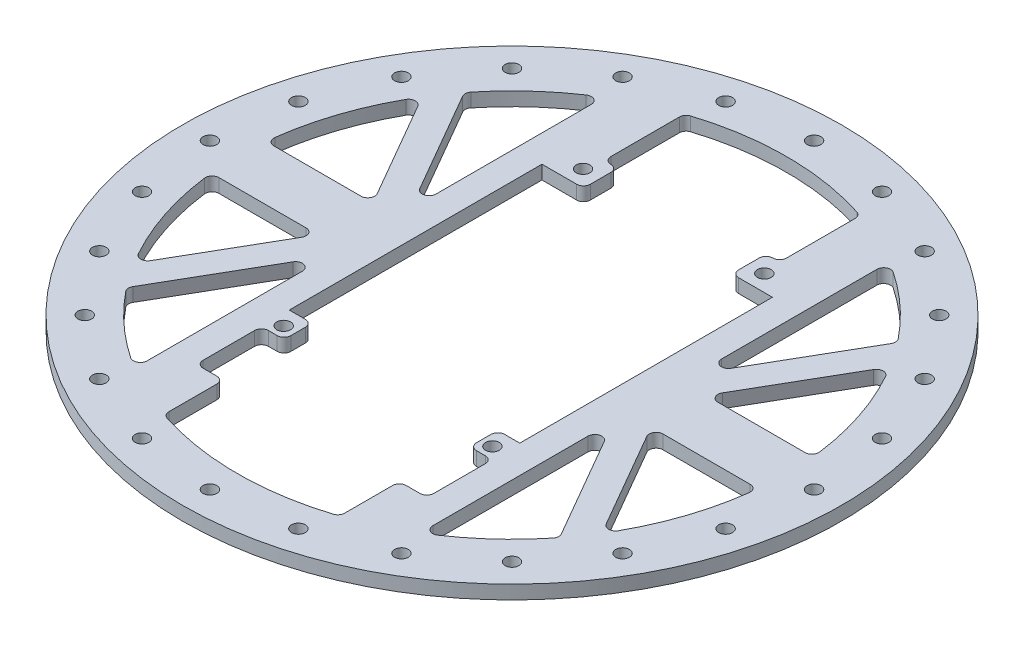
SolidWorks part; units mm, degrees
ref_plane "Front Plane" through (0, 0, 0) normal (0, 0, 1) x (1, 0, 0)
ref_plane "Top Plane" through (0, 0, 0) normal (0, 1, 0) x (1, 0, 0)
ref_plane "Right Plane" through (0, 0, 0) normal (1, 0, 0) x (0, 0, -1)
sketch "Model" plane through (0, 0, 0) normal (0, 1, 0) x (1, 0, 0)
  line L0 (-39.8941, -8.7312) -> (-52.7093, -30.9279)
  line L1 (-61.4016, -6.35) -> (-41.2689, -6.35)
  line L2 (39.8941, 8.7312) -> (52.7093, 30.9279)
  line L3 (61.4016, 6.35) -> (41.2689, 6.35)
  line L4 (-35.9823, 14.6559) -> (-49.5294, 38.1202)
  line L5 (-33.02, 51.3369) -> (-33.02, 15.4496)
  line L6 (41.2689, -6.35) -> (61.4016, -6.35)
  line L7 (52.7093, -30.9279) -> (39.8941, -8.7313)
  line L8 (17.145, 39.9977) -> (17.1433, 35.2712)
  line L9 (20.32, 59.0106) -> (20.32, 43.1727)
  line L10 (-20.32, 43.1727) -> (-20.32, 59.0106)
  line L11 (-17.145, 35.2653) -> (-17.145, 39.9977)
  line L12 (-26.7518, 33.6778) -> (-18.7325, 33.6778)
  line L13 (-26.7518, -24.7422) -> (-26.7518, 33.6778)
  line L14 (-23.0425, -24.7422) -> (-26.7518, -24.7422)
  line L15 (-21.455, -29.6672) -> (-21.455, -26.3297)
  line L16 (-25.0825, -31.2547) -> (-23.0425, -31.2547)
  line L17 (-26.67, -44.7675) -> (-26.67, -32.8422)
  line L18 (-21.9075, -46.355) -> (-25.0825, -46.355)
  line L19 (-20.32, -59.0106) -> (-20.32, -47.9425)
  line L20 (20.32, -47.9425) -> (20.32, -59.0106)
  line L21 (25.0825, -46.355) -> (21.9075, -46.355)
  line L22 (26.67, -32.8422) -> (26.67, -44.7675)
  line L23 (23.0425, -31.2547) -> (25.0825, -31.2547)
  line L24 (21.455, -26.3297) -> (21.455, -29.6672)
  line L25 (26.5374, -24.7422) -> (23.0425, -24.7422)
  line L26 (26.5374, 33.6778) -> (26.5374, -24.7422)
  line L27 (18.7308, 33.6778) -> (26.5374, 33.6778)
  line L28 (33.02, 15.4496) -> (33.02, 51.3369)
  line L29 (49.5294, 38.1202) -> (35.9823, 14.6559)
  line L30 (35.9823, -14.6559) -> (49.5294, -38.1202)
  line L31 (33.02, -51.3369) -> (33.02, -15.4496)
  line L32 (-49.5294, -38.1202) -> (-35.9823, -14.6559)
  line L33 (-33.02, -15.4496) -> (-33.02, -51.3369)
  line L34 (-41.2689, 6.35) -> (-61.4016, 6.35)
  line L35 (-52.7093, 30.9279) -> (-39.8941, 8.7312)
  circle A0 centre (-21.0623, 37.4877) radius 1.5875
  circle A1 centre (24.0227, -28.5523) radius 1.5875
  circle A2 centre (-34.925, -60.4919) radius 1.5875
  circle A3 centre (-60.4919, -34.925) radius 1.5875
  circle A4 centre (-69.85, 0) radius 1.5875
  circle A5 centre (-60.4919, 34.925) radius 1.5875
  circle A6 centre (0, 69.85) radius 1.5875
  circle A7 centre (34.925, 60.4919) radius 1.5875
  circle A8 centre (60.4919, 34.925) radius 1.5875
  circle A9 centre (69.85, 0) radius 1.5875
  circle A10 centre (60.4919, -34.925) radius 1.5875
  circle A11 centre (34.925, -60.4919) radius 1.5875
  circle A12 centre (-24.2373, -28.5523) radius 1.5875
  circle A13 centre (0, 0) radius 76.2
  circle A14 centre (0, -69.85) radius 1.5875
  circle A15 centre (18.0785, -67.4699) radius 1.5875
  circle A16 centre (49.3914, -49.3914) radius 1.5875
  circle A17 centre (67.4699, -18.0785) radius 1.5875
  circle A18 centre (67.4699, 18.0785) radius 1.5875
  circle A19 centre (49.3914, 49.3914) radius 1.5875
  circle A20 centre (18.0785, 67.4699) radius 1.5875
  circle A21 centre (-18.0785, 67.4699) radius 1.5875
  circle A22 centre (-49.3914, 49.3914) radius 1.5875
  circle A23 centre (-67.4699, 18.0785) radius 1.5875
  circle A24 centre (-67.4699, -18.0785) radius 1.5875
  circle A25 centre (-49.3914, -49.3914) radius 1.5875
  circle A26 centre (-18.0785, -67.4699) radius 1.5875
  circle A27 centre (20.8477, 37.4877) radius 1.5875
  circle A28 centre (-34.925, 60.4919) radius 1.5875
  arc A29 (-39.8941, -8.7312) -> (-41.2689, -6.35) centre (-41.2689, -7.9375) ccw
  arc A30 (-61.4016, -6.35) -> (-62.976, -8.141) centre (-61.4016, -7.9375) ccw
  arc A31 (-62.976, -8.141) -> (-55.4709, -30.9068) centre (0, 0) ccw
  arc A32 (-55.4709, -30.9068) -> (-52.7093, -30.9279) centre (-54.0841, -30.1341) ccw
  arc A33 (39.8941, 8.7312) -> (41.2689, 6.35) centre (41.2689, 7.9375) ccw
  arc A34 (61.4016, 6.35) -> (62.976, 8.141) centre (61.4016, 7.9375) ccw
  arc A35 (62.976, 8.141) -> (55.4709, 30.9068) centre (0, 0) ccw
  arc A36 (55.4709, 30.9068) -> (52.7093, 30.9279) centre (54.0841, 30.1341) ccw
  arc A37 (-35.4949, 52.6532) -> (-49.3893, 39.9117) centre (0, 0) ccw
  arc A38 (-49.3893, 39.9117) -> (-49.5294, 38.1202) centre (-48.1546, 38.9139) ccw
  arc A39 (-35.9823, 14.6559) -> (-33.02, 15.4496) centre (-34.6075, 15.4496) ccw
  arc A40 (-33.02, 51.3369) -> (-35.4949, 52.6532) centre (-34.6075, 51.3369) ccw
  arc A41 (55.4709, -30.9068) -> (62.976, -8.141) centre (0, 0) ccw
  arc A42 (62.976, -8.141) -> (61.4016, -6.35) centre (61.4016, -7.9375) ccw
  arc A43 (41.2689, -6.35) -> (39.8941, -8.7313) centre (41.2689, -7.9375) ccw
  arc A44 (52.7093, -30.9279) -> (55.4709, -30.9068) centre (54.0841, -30.1341) ccw
  arc A45 (18.7325, 41.5852) -> (17.145, 39.9977) centre (18.7325, 39.9977) ccw
  arc A46 (18.7325, 41.5852) -> (20.32, 43.1727) centre (18.7325, 43.1727) ccw
  arc A47 (20.32, 59.0106) -> (19.2128, 60.5237) centre (18.7325, 59.0106) ccw
  arc A48 (19.2128, 60.5237) -> (-19.2128, 60.5237) centre (0, 0) ccw
  arc A49 (-19.2128, 60.5237) -> (-20.32, 59.0106) centre (-18.7325, 59.0106) ccw
  arc A50 (-20.32, 43.1727) -> (-18.7325, 41.5852) centre (-18.7325, 43.1727) ccw
  arc A51 (-17.145, 39.9977) -> (-18.7325, 41.5852) centre (-18.7325, 39.9977) ccw
  arc A52 (-18.7325, 33.6778) -> (-17.145, 35.2653) centre (-18.7325, 35.2653) ccw
  arc A53 (-21.455, -26.3297) -> (-23.0425, -24.7422) centre (-23.0425, -26.3297) ccw
  arc A54 (-23.0425, -31.2547) -> (-21.455, -29.6672) centre (-23.0425, -29.6672) ccw
  arc A55 (-25.0825, -31.2547) -> (-26.67, -32.8422) centre (-25.0825, -32.8422) ccw
  arc A56 (-26.67, -44.7675) -> (-25.0825, -46.355) centre (-25.0825, -44.7675) ccw
  arc A57 (-20.32, -47.9425) -> (-21.9075, -46.355) centre (-21.9075, -47.9425) ccw
  arc A58 (-20.32, -59.0106) -> (-19.2128, -60.5237) centre (-18.7325, -59.0106) ccw
  arc A59 (-19.2128, -60.5237) -> (19.2128, -60.5237) centre (0, 0) ccw
  arc A60 (19.2128, -60.5237) -> (20.32, -59.0106) centre (18.7325, -59.0106) ccw
  arc A61 (21.9075, -46.355) -> (20.32, -47.9425) centre (21.9075, -47.9425) ccw
  arc A62 (25.0825, -46.355) -> (26.67, -44.7675) centre (25.0825, -44.7675) ccw
  arc A63 (26.67, -32.8422) -> (25.0825, -31.2547) centre (25.0825, -32.8422) ccw
  arc A64 (21.455, -29.6672) -> (23.0425, -31.2547) centre (23.0425, -29.6672) ccw
  arc A65 (23.0425, -24.7422) -> (21.455, -26.3297) centre (23.0425, -26.3297) ccw
  arc A66 (17.1433, 35.2712) -> (18.7308, 33.6778) centre (18.7308, 35.2653) ccw
  arc A67 (33.02, 15.4496) -> (35.9823, 14.6559) centre (34.6075, 15.4496) ccw
  arc A68 (49.5294, 38.1202) -> (49.3893, 39.9117) centre (48.1546, 38.9139) ccw
  arc A69 (49.3893, 39.9117) -> (35.4949, 52.6532) centre (0, 0) ccw
  arc A70 (35.4949, 52.6532) -> (33.02, 51.3369) centre (34.6075, 51.3369) ccw
  arc A71 (35.9823, -14.6559) -> (33.02, -15.4496) centre (34.6075, -15.4496) ccw
  arc A72 (33.02, -51.3369) -> (35.4949, -52.6532) centre (34.6075, -51.3369) ccw
  arc A73 (35.4949, -52.6532) -> (49.3893, -39.9117) centre (0, 0) ccw
  arc A74 (49.3893, -39.9117) -> (49.5294, -38.1202) centre (48.1546, -38.9139) ccw
  arc A75 (-49.5294, -38.1202) -> (-49.3893, -39.9117) centre (-48.1546, -38.9139) ccw
  arc A76 (-49.3893, -39.9117) -> (-35.4949, -52.6532) centre (0, 0) ccw
  arc A77 (-35.4949, -52.6532) -> (-33.02, -51.3369) centre (-34.6075, -51.3369) ccw
  arc A78 (-33.02, -15.4496) -> (-35.9823, -14.6559) centre (-34.6075, -15.4496) ccw
  arc A79 (-55.4709, 30.9068) -> (-62.976, 8.141) centre (0, 0) ccw
  arc A80 (-62.976, 8.141) -> (-61.4016, 6.35) centre (-61.4016, 7.9375) ccw
  arc A81 (-41.2689, 6.35) -> (-39.8941, 8.7312) centre (-41.2689, 7.9375) ccw
  arc A82 (-52.7093, 30.9279) -> (-55.4709, 30.9068) centre (-54.0841, 30.1341) ccw
extrude "Boss-Extrude1" add sketch "Model" along normal blind 3.175
